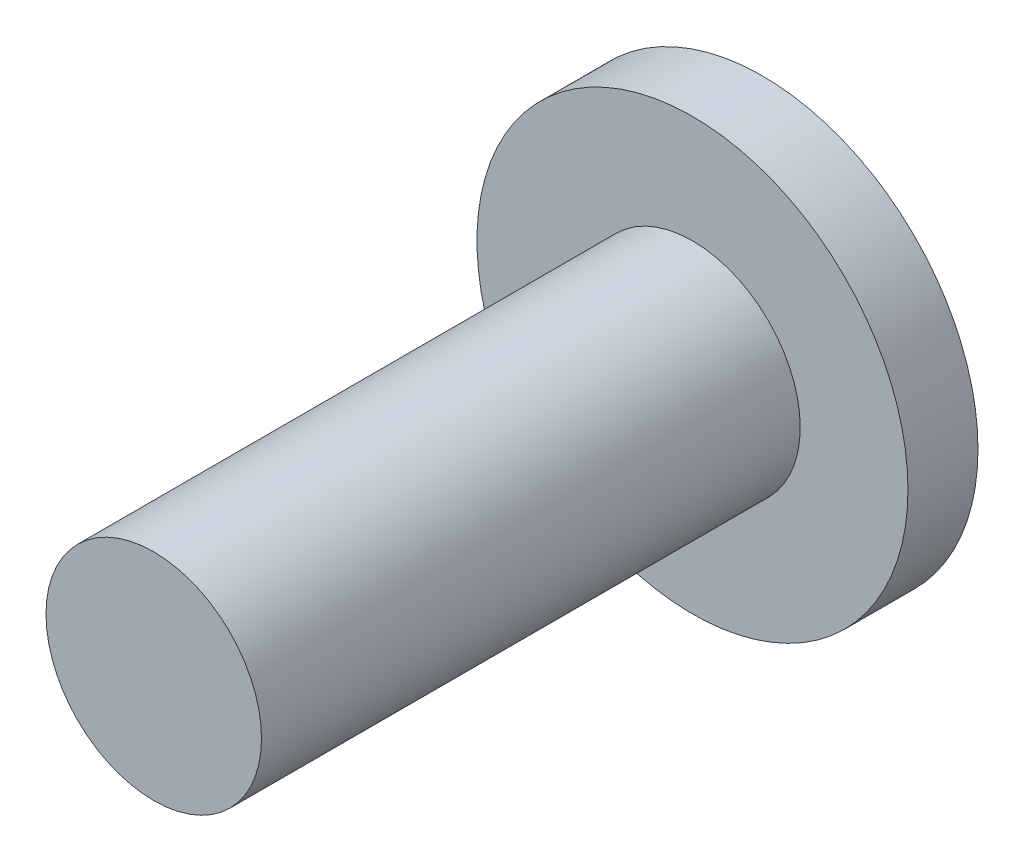
SolidWorks part; units mm, degrees
material "AISI 304"
ref_plane "前视基准面" through (0, 0, 0) normal (0, 0, 1) x (1, 0, 0)
ref_plane "上视基准面" through (0, 0, 0) normal (0, 1, 0) x (1, 0, 0)
ref_plane "右视基准面" through (0, 0, 0) normal (1, 0, 0) x (0, 0, -1)
other "Configuration Table"
sketch "草图1" plane through (0, 0, 0) normal (0, 0, 1) x (1, 0, 0)
  circle A0 centre (0, 0) radius 4
  dimension "D1" = 8
extrude "凸台-拉伸1" add sketch "草图1" along normal blind 1.3
sketch "草图2" plane through (0, 0, 1.3) normal (0, 0, 1) x (1, 0, 0)
  circle A0 centre (0, 0) radius 2
  dimension "D1" = 4
extrude "凸台-拉伸2" add sketch "草图2" along normal blind 10
sketch "草图3" plane through (0, 0, 0) normal (0, 0, -1) x (-1, 0, 0)
  line L1 (1.4434, 0) -> (0.7217, 1.25)
  line L2 (0.7217, 1.25) -> (-0.7217, 1.25)
  line L3 (-0.7217, 1.25) -> (-1.4434, 0)
  line L4 (-1.4434, 0) -> (-0.7217, -1.25)
  line L5 (-0.7217, -1.25) -> (0.7217, -1.25)
  line L6 (0.7217, -1.25) -> (1.4434, 0)
  circle A0 centre (0, 0) radius 1.25 construction
extrude "切除-拉伸1" cut sketch "草图3" against normal blind 1
